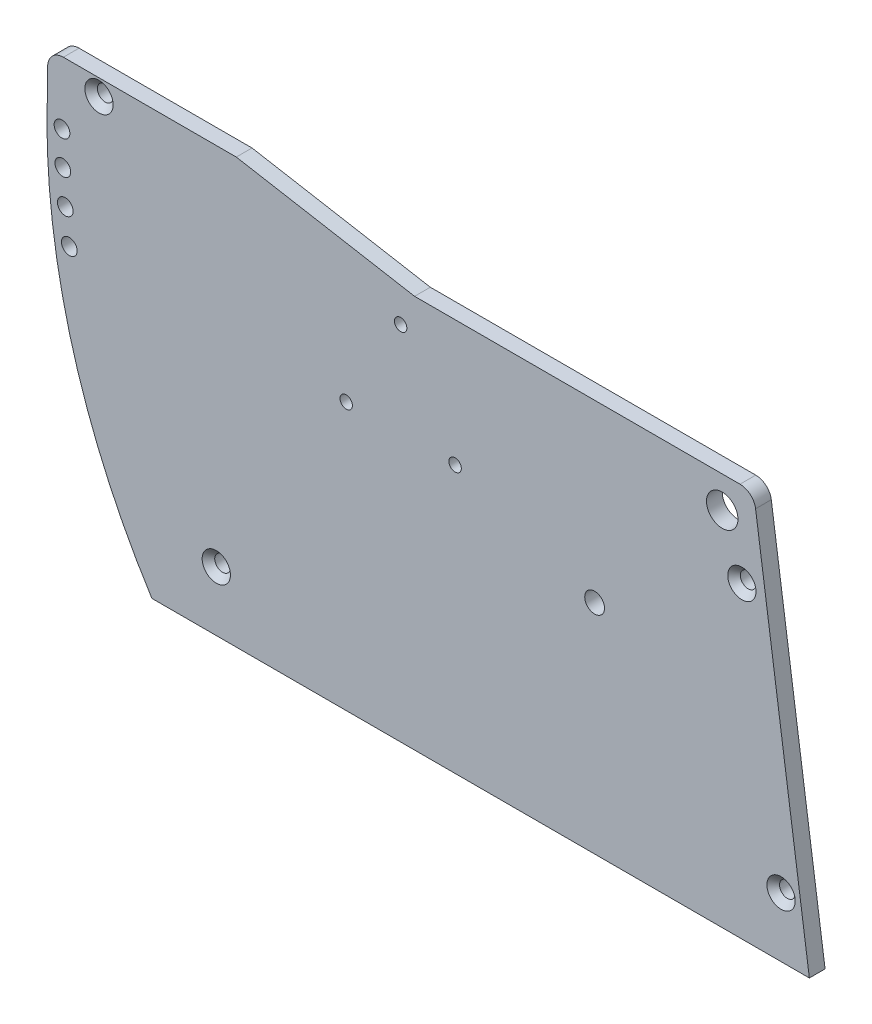
SolidWorks part; units mm, degrees
ref_plane "Front Plane" through (0, 0, 0) normal (0, 0, 1) x (1, 0, 0)
ref_plane "Top Plane" through (0, 0, 0) normal (0, 1, 0) x (1, 0, 0)
ref_plane "Right Plane" through (0, 0, 0) normal (1, 0, 0) x (0, 0, -1)
sketch "Sketch18" plane through (0, 0, 0) normal (0, 0, 1) x (1, 0, 0)
  line L0 (0, 0) -> (-265.6047, 0)
  line L1 (-165.1, 120.65) -> (-165.1, 146.05) construction
  line L4 (0, 0) -> (-21.7272, 153.2911)
  line L5 (-28.0144, 158.75) -> (-159.4738, 158.75)
  line L6 (-159.4738, 158.75) -> (-231.4991, 171.45)
  line L7 (-231.4991, 171.45) -> (-301.3491, 171.45)
  line L8 (-307.6991, 165.1) -> (-307.6991, 158.75)
  circle A0 centre (-35.2009, 146.05) radius 266.7 construction
  arc A1 (-307.6991, 158.75) -> (-265.6047, 0) centre (-35.2009, 146.05) ccw
  arc A2 (-21.7272, 153.2911) -> (-28.0144, 158.75) centre (-28.0144, 152.4) ccw
  arc A3 (-301.3491, 171.45) -> (-307.6991, 165.1) centre (-301.3491, 165.1) ccw
  circle A4 centre (-11.4235, 24.0347) radius 3.175
  circle A5 centre (-27.2534, 124.4065) radius 3.175
  circle A6 centre (-35.2009, 146.05) radius 6.35
  circle A7 centre (-301.9009, 146.05) radius 3.175
  circle A8 centre (-301.5697, 132.7614) radius 3.175
  circle A9 centre (-300.5799, 119.5375) radius 3.175
  circle A10 centre (-298.9435, 106.4428) radius 3.175
  circle A11 centre (-239.5689, 24.0347) radius 3.175
  circle A12 centre (-286.9621, 164.8507) radius 3.175
  circle A13 centre (-165.1, 146.05) radius 2.5019
  circle A14 centre (-143.103, 107.95) radius 2.5019
  circle A15 centre (-165.1, 120.65) radius 1.5875 construction
  circle A16 centre (-187.097, 107.95) radius 2.5019
  point P40 (-165.1, 120.65)
  dimension "D7" = 13.2886
  dimension "D8" = 13.2239
  dimension "D9" = 13.0947
  dimension "D10" = 5.0038
  dimension "D11" = 6.35
  dimension "D12" = 20.7369
  dimension "D16" = 6.35
  dimension "D17" = 6.35
  dimension "D18" = 25.4
  dimension "D19" = 3
  dimension "D5" = 3.175
  dimension "D2" = 158.75
  dimension "D3" = 81.933
  dimension "D4" = 12.7
  dimension "D6" = 25.4
  dimension "D13" = 6.5993
  dimension "D14" = 76.2
  dimension "D15" = 72.0253
extrude "Boss-Extrude4" add sketch "Sketch18" along normal blind 6.35 separate body
chamfer "Chamfer1" distance 2.54 angle 45 4 edges at (-283.7871, 164.8507, 6.35) (-236.3939, 24.0347, 6.35) (-8.2485, 24.0347, 6.35) (-24.0784, 124.4065, 6.35)
sketch "Sketch19" plane through (0, 0, 0) normal (0, 0, -1) x (-1, 0, 0)
  circle A0 centre (86.7472, 87.9531) radius 4
extrude "Cut-Extrude1" cut sketch "Sketch19" against normal blind 43.434
